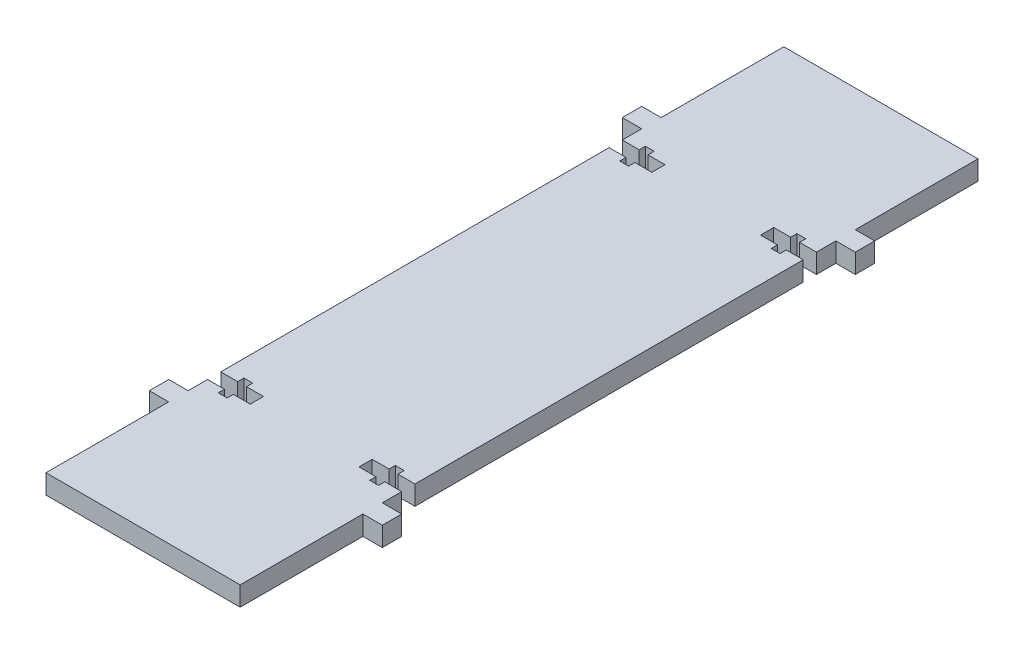
SolidWorks part; units mm, degrees
ref_plane "Front Plane" through (0, 0, 0) normal (0, 0, 1) x (1, 0, 0)
ref_plane "Top Plane" through (0, 0, 0) normal (0, 1, 0) x (1, 0, 0)
ref_plane "Right Plane" through (0, 0, 0) normal (1, 0, 0) x (0, 0, -1)
sketch "Elevator Belt Backplate" plane through (0, 0, 0) normal (0, 1, 0) x (1, 0, 0)
  line L0 (-31.75, 0) -> (31.75, 0) construction
  line L1 (-31.75, -120.65) -> (31.75, -120.65)
  line L2 (-31.75, -120.65) -> (-31.75, -80.518)
  line L3 (-31.75, 120.65) -> (31.75, 120.65)
  line L4 (31.75, -120.65) -> (31.75, -80.518)
  line L5 (-31.75, -120.65) -> (31.75, 120.65) construction
  line L6 (-31.75, 120.65) -> (31.75, -120.65) construction
  line L7 (31.75, 80.518) -> (31.75, 120.65)
  line L8 (31.75, 74.168) -> (38.1, 74.168)
  line L9 (0, 120.65) -> (0, -120.65) construction
  line L10 (31.75, 80.518) -> (38.1, 80.518)
  line L11 (38.1, 74.168) -> (38.1, 80.518)
  line L12 (31.75, -80.518) -> (38.1, -80.518)
  line L13 (38.1, -74.168) -> (38.1, -80.518)
  line L14 (31.75, -74.168) -> (38.1, -74.168)
  line L15 (-31.75, 80.518) -> (-38.1, 80.518)
  line L16 (-31.75, -74.168) -> (-38.1, -74.168)
  line L17 (-38.1, -74.168) -> (-38.1, -80.518)
  line L18 (-31.75, -80.518) -> (-38.1, -80.518)
  line L19 (-38.1, 74.168) -> (-38.1, 80.518)
  line L20 (-31.75, 74.168) -> (-38.1, 74.168)
  line L21 (-31.75, 80.518) -> (-31.75, 120.65)
  line L22 (-31.75, -74.168) -> (-31.75, -67.818)
  line L23 (31.75, -74.168) -> (31.75, -67.818)
  line L24 (-31.75, 67.818) -> (-26.215, 67.818)
  line L25 (-26.215, 67.818) -> (-26.215, 69.859)
  line L26 (-26.215, 69.859) -> (-23.315, 69.859)
  line L27 (-23.315, 69.859) -> (-23.315, 67.818)
  line L28 (-23.315, 67.818) -> (-17.78, 67.818)
  line L29 (-17.78, 67.818) -> (-17.78, 63.5)
  line L30 (-17.78, 63.5) -> (-23.315, 63.5)
  line L31 (-23.315, 63.5) -> (-23.315, 61.459)
  line L32 (-23.315, 61.459) -> (-26.215, 61.459)
  line L33 (-26.215, 61.459) -> (-26.215, 63.5)
  line L34 (-26.215, 63.5) -> (-31.75, 63.5)
  line L35 (-31.75, 67.818) -> (-31.75, 74.168)
  line L36 (31.75, 67.818) -> (26.215, 67.818)
  line L37 (23.315, 69.859) -> (23.315, 67.818)
  line L38 (26.215, 67.818) -> (26.215, 69.859)
  line L39 (26.215, 69.859) -> (23.315, 69.859)
  line L40 (23.315, 67.818) -> (17.78, 67.818)
  line L41 (26.215, 63.5) -> (31.75, 63.5)
  line L42 (26.215, 61.459) -> (26.215, 63.5)
  line L43 (23.315, 61.459) -> (26.215, 61.459)
  line L44 (23.315, 63.5) -> (23.315, 61.459)
  line L45 (17.78, 63.5) -> (23.315, 63.5)
  line L46 (17.78, 67.818) -> (17.78, 63.5)
  line L47 (31.75, 67.818) -> (31.75, 74.168)
  line L48 (26.215, -63.5) -> (31.75, -63.5)
  line L49 (31.75, -67.818) -> (26.215, -67.818)
  line L50 (17.78, -63.5) -> (23.315, -63.5)
  line L51 (17.78, -67.818) -> (17.78, -63.5)
  line L52 (23.315, -67.818) -> (17.78, -67.818)
  line L53 (23.315, -63.5) -> (23.315, -61.459)
  line L54 (23.315, -61.459) -> (26.215, -61.459)
  line L55 (26.215, -61.459) -> (26.215, -63.5)
  line L56 (26.215, -69.859) -> (23.315, -69.859)
  line L57 (26.215, -67.818) -> (26.215, -69.859)
  line L58 (23.315, -69.859) -> (23.315, -67.818)
  line L59 (-17.78, -67.818) -> (-17.78, -63.5)
  line L60 (-26.215, -63.5) -> (-31.75, -63.5)
  line L61 (-26.215, -61.459) -> (-26.215, -63.5)
  line L62 (-23.315, -61.459) -> (-26.215, -61.459)
  line L63 (-23.315, -63.5) -> (-23.315, -61.459)
  line L64 (-17.78, -63.5) -> (-23.315, -63.5)
  line L65 (-23.315, -67.818) -> (-17.78, -67.818)
  line L66 (-23.315, -69.859) -> (-23.315, -67.818)
  line L67 (-26.215, -69.859) -> (-23.315, -69.859)
  line L68 (-26.215, -67.818) -> (-26.215, -69.859)
  line L69 (-31.75, -67.818) -> (-26.215, -67.818)
  line L70 (31.75, -63.5) -> (31.75, 63.5)
  line L71 (-31.75, -63.5) -> (-31.75, 63.5)
  point P0 (0, 0)
  point P26 (-94.3248, 77.7538)
  dimension "D1" = 6.35
  dimension "D2" = 6.35
  dimension "D3" = 6.35
  dimension "D4" = 63.5
  dimension "D5" = 241.3
  dimension "D6" = 4.318
  dimension "D7" = 2.9
  dimension "D8" = 8.4
  dimension "D9" = 13.97
  dimension "D10" = 63.5
extrude "Boss-Extrude1" add sketch "Elevator Belt Backplate" along normal blind 6.35
equation "\"Ball Diameter\"= 1.75in"
equation "\"Sheet Thickness\"= 0.25in"
equation "\"Screw Diameter\"= .17in"
equation "\"Robot Diameter\"= 14in"
equation "\"Castor Screw Diameter\"= 0.22in"
equation "\"Wheel Diameter\" = 4in"
equation "\"Nut Diameter\" = 8.4mm"
equation "\"Nut Height\" = 2.9mm"
equation "\"Screw Height\" = 0.55in"
equation "\"Pulley Diameter\" = 1in"
equation "\"Reactor Height\" = 14in"
equation "\"Elevator Height\" = 11.5in"
equation "\"Elevator Width\" = \"Ball Diameter\" + 0.25in"
equation "\"Elevator Bearing Diameter\" = sqr(2*(\"Sheet Thickness\"^2)) + 0.2in"
equation "\"Elevator Axle Length\" = \"Elevator Width\" + 8*\"Sheet Thickness\""
equation "\"D7@Elevator Belt Backplate\"=\"Sheet Thickness\""
equation "\"D8@Elevator Belt Backplate\"=\"Sheet Thickness\""
equation "\"D4@Elevator Belt Backplate\"=\"Elevator Width\" + 2 * \"Sheet Thickness\""
equation "\"D5@Elevator Belt Backplate\"=\"Elevator Height\"-\"Pulley Diameter\"-1in"
equation "\"D1@Boss-Extrude1\"=\"Sheet Thickness\""
equation "\"D6@Elevator Belt Backplate\" = \"Screw Diameter\""
equation "\"D7@Elevator Belt Backplate\"=\"Nut Height\""
equation "\"D8@Elevator Belt Backplate\"=\"Nut Diameter\""
equation "\"D9@Elevator Belt Backplate\"=\"Screw Height\""
